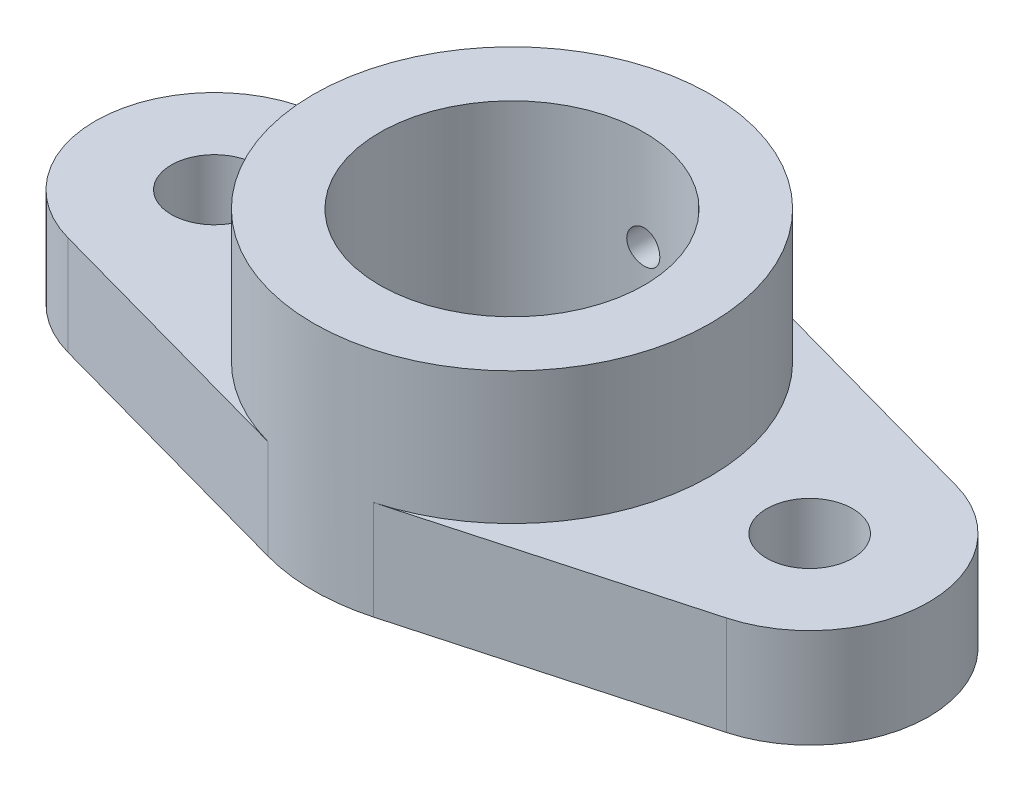
SolidWorks part; units mm, degrees
ref_plane "Ön Düzlem" through (0, 0, 0) normal (0, 0, 1) x (1, 0, 0)
ref_plane "Üst Düzlem" through (0, 0, 0) normal (0, 1, 0) x (1, 0, 0)
ref_plane "Sağ Düzlem" through (0, 0, 0) normal (1, 0, 0) x (0, 0, -1)
sketch "Çizim1" plane through (0, 0, 0) normal (0, 1, 0) x (1, 0, 0)
  line L0 (0, -72.9844) -> (0, 68.3431) construction
  line L1 (-49.8, 17.3482) -> (-8, 28.9137)
  line L2 (-45, 0) -> (82.7348, 0) construction
  line L3 (49.8, 17.3482) -> (8, 28.9137)
  line L4 (-49.8, -17.3482) -> (-8, -28.9137)
  line L5 (49.8, -17.3482) -> (8, -28.9137)
  circle A1 centre (-45, 0) radius 6.5
  arc A2 (-49.8, 17.3482) -> (-49.8, -17.3482) centre (-45, 0) ccw
  circle A3 centre (45, 0) radius 6.5
  arc A4 (49.8, 17.3482) -> (49.8, -17.3482) centre (45, 0) cw
  arc A5 (8, 28.9137) -> (-8, 28.9137) centre (0, 0) ccw
  arc A6 (-8, -28.9137) -> (8, -28.9137) centre (0, 0) ccw
  point P1 (0, 30)
  dimension "D1" = 30
  dimension "D3" = 13
  dimension "D4" = 18
  dimension "D2" = 45
  dimension "D5" = 30.932
extrude "Yükseklik-Ekstrüzyon2" add sketch "Çizim1" along normal blind 15
sketch "Çizim2" plane through (0, 15, 0) normal (0, 1, 0) x (1, 0, 0)
  circle A0 centre (0, 0) radius 30
extrude "Yükseklik-Ekstrüzyon3" add sketch "Çizim2" along normal blind 20
sketch "Çizim3" plane through (0, 35, 0) normal (0, 1, 0) x (1, 0, 0)
  circle A0 centre (0, 0) radius 20
  dimension "D1" = 40
extrude "Kes-Ekstrüzyon2" cut sketch "Çizim3" against normal blind 83 contours A0
ref_plane "Düzlem2" through (0, 0, -30) normal (0, 0, -1) x (-1, 0, 0)
sketch "Çizim4" plane through (0, 0, -30) normal (0, 0, -1) x (-1, 0, 0)
  line L0 (30, 35) -> (-30, 35) construction
  circle A0 centre (0, 20) radius 2.5
  dimension "D1" = 5
  dimension "D2" = 0
  dimension "D3" = 15
extrude "Kes-Ekstrüzyon3" cut sketch "Çizim4" against normal blind 15
